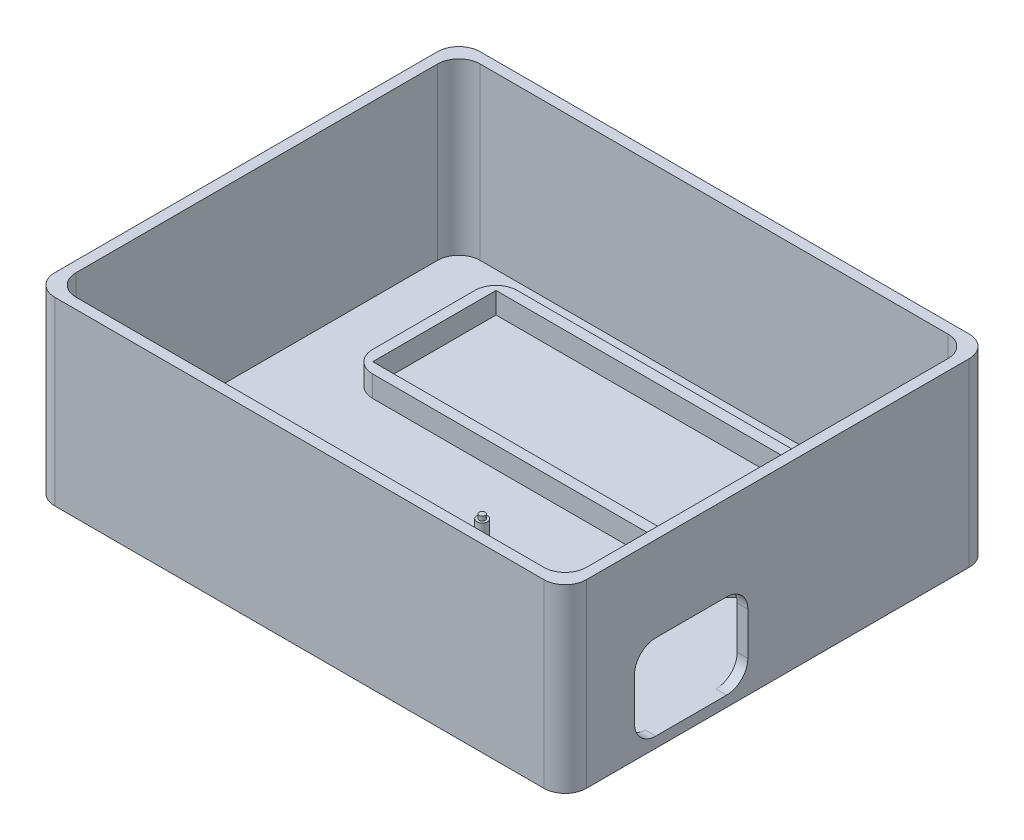
SolidWorks part; units mm, degrees
ref_plane "Front Plane" through (0, 0, 0) normal (0, 0, 1) x (1, 0, 0)
ref_plane "Top Plane" through (0, 0, 0) normal (0, 1, 0) x (1, 0, 0)
ref_plane "Right Plane" through (0, 0, 0) normal (1, 0, 0) x (0, 0, -1)
sketch "Sketch2" plane through (0, 0, 0) normal (0, 1, 0) x (1, 0, 0)
  line L1 (-125, -100) -> (125, -100)
  line L2 (-125, -100) -> (-125, 100)
  line L3 (-125, 100) -> (125, 100)
  line L4 (125, -100) -> (125, 100)
  line L5 (-125, -100) -> (125, 100) construction
  line L6 (-125, 100) -> (125, -100) construction
  point P0 (0, 0)
  dimension "D1" = 200
  dimension "D2" = 250
extrude "Boss-Extrude1" add sketch "Sketch2" along normal blind 5
sketch "Sketch3" plane through (0, 5, 0) normal (0, 1, 0) x (1, 0, 0)
  line L0 (-125, 100) -> (125, 100)
  line L1 (125, 100) -> (125, -100)
  line L2 (125, -100) -> (-125, -100)
  line L3 (-125, -100) -> (-125, 100)
  line L4 (-120, -95) -> (-120, 95)
  line L5 (-120, 95) -> (120, 95)
  line L6 (120, 95) -> (120, -95)
  line L7 (120, -95) -> (-120, -95)
  dimension "D1" = 5
extrude "Boss-Extrude2" add sketch "Sketch3" along normal blind 80
sketch "Sketch1" plane through (0, 5, 0) normal (0, 1, 0) x (1, 0, 0)
  line L0 (-84, 18.5) -> (-84, 76.5)
  line L1 (-84, 76.5) -> (84, 76.5)
  line L2 (84, 76.5) -> (84, 18.5)
  line L3 (84, 18.5) -> (-84, 18.5)
  line L4 (-89, 13.5) -> (-89, 81.5)
  line L5 (-89, 81.5) -> (89, 81.5)
  line L6 (89, 81.5) -> (89, 13.5)
  line L7 (89, 13.5) -> (-89, 13.5)
  line L12 (120, 95) -> (-120, 95) construction
  line L13 (0, 0) -> (0, 95) construction
  line L14 (120, 95) -> (-120, 95) construction
  point P10 (0, 95)
  point P11 (0, 81.5)
  point P16 (84, 47.5)
  point P17 (0, 47.5)
  dimension "D1" = 168
  dimension "D2" = 58
  dimension "D3" = 5
extrude "Boss-Extrude3" add sketch "Sketch1" along normal blind 10
sketch "Sketch6" plane through (0, 5, 0) normal (0, 1, 0) x (1, 0, 0)
  line L0 (89, 13.5) -> (89, -95) construction
  line L1 (-12.6, -14.1) -> (89, -14.1)
  line L2 (-12.6, -14.1) -> (-12.6, -67.4)
  line L3 (-12.6, -67.4) -> (89, -67.4)
  line L4 (89, -14.1) -> (89, -67.4)
  line L5 (-120, -95) -> (120, -95) construction
  point P9 (89, -40.75)
  point P10 (89, -40.75)
  point P11 (1.4, -64.9)
  point P12 (2.7, -16.7)
  point P13 (53.5, -31.9)
  point P14 (53.5, -59.8)
  point P15 (77.6, -16.7)
  point P16 (83.95, -64.9)
  point P17 (10.6506, -41.0007)
  point P18 (0, 0)
  point P19 (0, 0)
  point P20 (0, 0)
  point P21 (2.7, -35.95)
  point P22 (0, 0)
  dimension "D1" = 53.3
  dimension "D2" = 101.6
  dimension "D3" = 14
  dimension "D4" = 1.3
  dimension "D5" = 50.8
  dimension "D6" = 24.1
  dimension "D7" = 15.2
  dimension "D8" = 27.9
  dimension "D9" = 5.1
  dimension "D10" = 2.5
  dimension "D11" = 82.55
sketch "Sketch7" plane through (0, 5, 0) normal (0, 1, 0) x (1, 0, 0)
  circle A0 centre (2.7, -16.7) radius 2.5
  circle A1 centre (1.4, -64.9) radius 2.5
  circle A2 centre (53.5, -31.9) radius 2.5
  circle A3 centre (77.6, -16.7) radius 2.5
  circle A4 centre (83.95, -64.9) radius 2.5
  circle A5 centre (53.5, -59.8) radius 2.5
  dimension "D1" = 5
extrude "Boss-Extrude4" add sketch "Sketch7" along normal blind 7
sketch "Sketch8" plane through (0, 12, 0) normal (0, 1, 0) x (1, 0, 0)
  circle A0 centre (2.7, -16.7) radius 1.4
  circle A1 centre (53.5, -31.9) radius 1.4
  circle A2 centre (77.6, -16.7) radius 1.4
  circle A3 centre (53.5, -59.8) radius 1.4
  circle A4 centre (1.4, -64.9) radius 1.4
  circle A5 centre (83.95, -64.9) radius 1.4
  dimension "D1" = 2.8
extrude "Boss-Extrude5" add sketch "Sketch8" along normal blind 2
sketch "Sketch4" plane through (125, 0, 0) normal (1, 0, 0) x (0, 0, -1)
  line L0 (-67.4, 45) -> (-14.1, 45)
  line L1 (-14.1, 45) -> (-14.1, 5)
  line L2 (-14.1, 5) -> (-67.4, 5)
  line L3 (-67.4, 5) -> (-67.4, 45)
  line L7 (-57.3, 5) -> (-62.3, 5) construction
  line L8 (-14.1, 5) -> (-67.4, 5) construction
  point P2 (-40.75, 5)
  point P7 (-40.75, 5)
  point P8 (0, 0)
  dimension "D1" = 40
extrude "Cut-Extrude1" cut sketch "Sketch4" against normal up to next
fillet "Fillet1" radius 10 16 edges at (122.5, 5, 14.1) (122.5, 5, 67.4) (122.5, 45, 14.1) (122.5, 45, 67.4) (89, 10, -13.5) (89, 10, -81.5) (-89, 10, -81.5) (-89, 10, -13.5) (-125, 42.5, -100) (125, 42.5, -100) (125, 42.5, 100) (-125, 42.5, 100) (120, 45, 95) (-120, 45, 95) (-120, 45, -95) (120, 45, -95)
